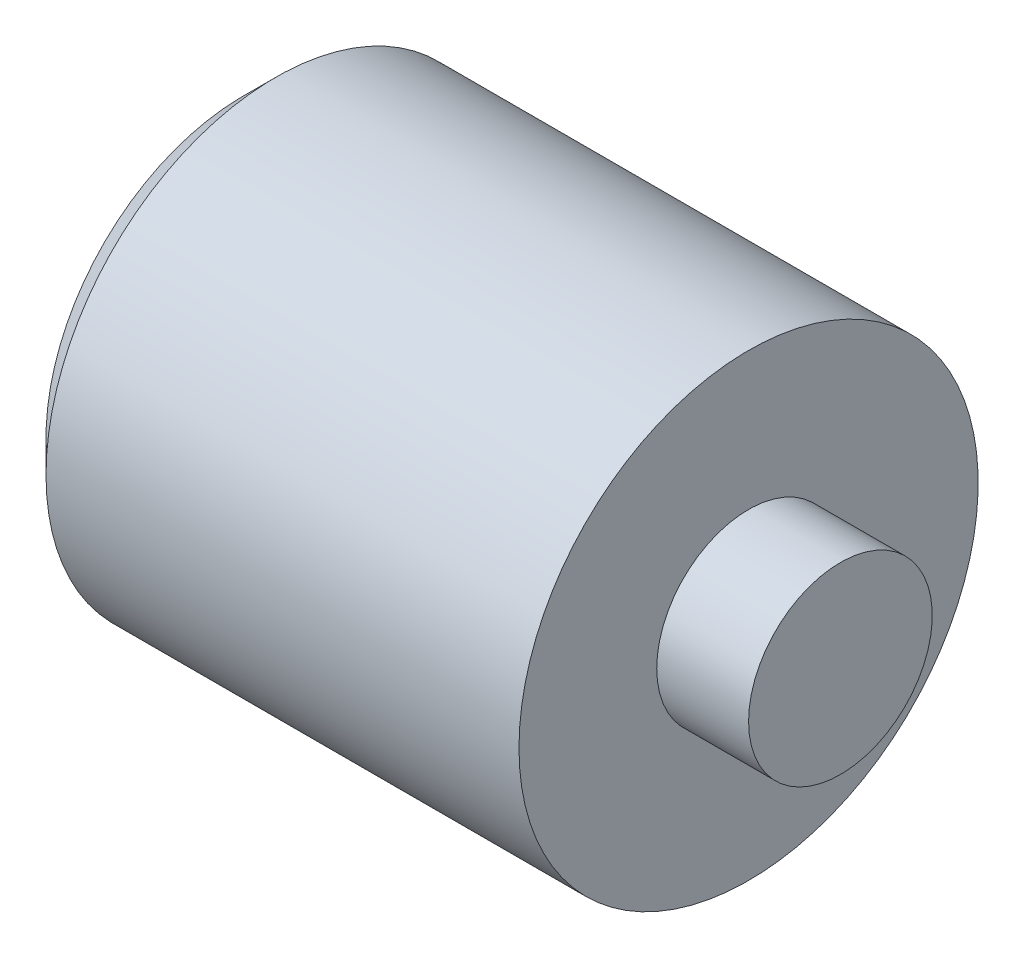
SolidWorks part; units mm, degrees
ref_plane "Plan1" through (0, 0, 0) normal (0, 0, 1) x (1, 0, 0)
ref_plane "Plan2" through (0, 0, 0) normal (0, 1, 0) x (1, 0, 0)
ref_plane "Plan3" through (0, 0, 0) normal (1, 0, 0) x (0, 0, -1)
sketch "Esquisse1" plane through (0, 0, 0) normal (0, 0, 1) x (1, 0, 0)
  line L0 (0, 5) -> (0, 0)
  line L1 (0, 5) -> (11, 5)
  line L2 (11, 5) -> (11, 2)
  line L3 (11, 2) -> (13, 2)
  line L4 (13, 2) -> (13, 0)
  line L6 (0, 0) -> (13, 0) construction
  line L7 (0, 0) -> (13, 0)
  dimension "D1" = 5
  dimension "D2" = 11
revolve "Base-Révolution" add sketch "Esquisse1" angle 360 about L6
chamfer "Chanfrein1" distance 0.7 angle 45
